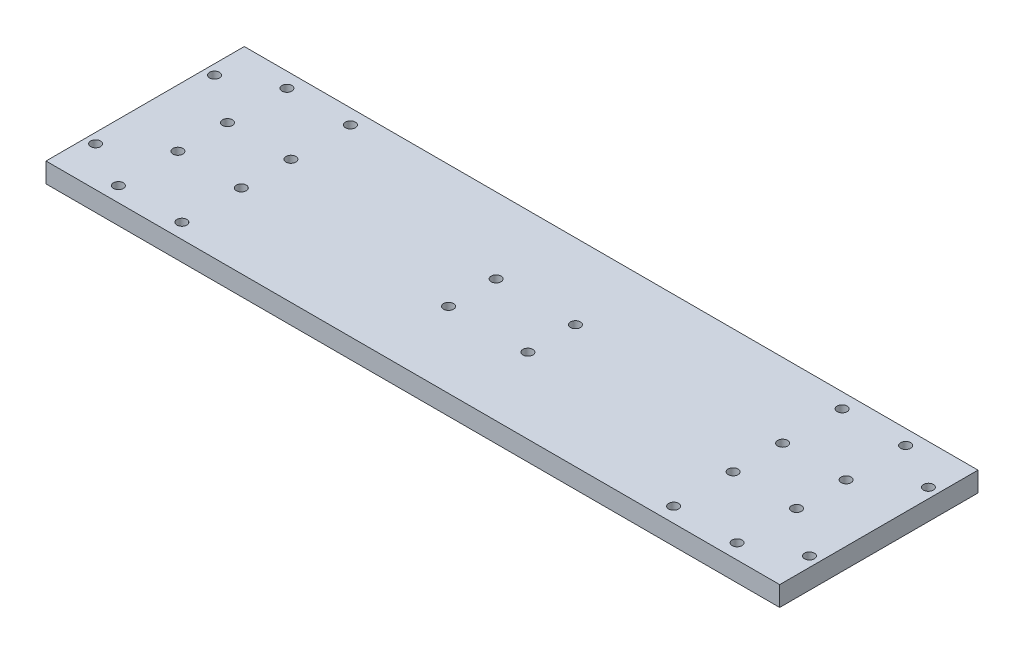
SolidWorks part; units mm, degrees
ref_plane "Front Plane" through (0, 0, 0) normal (0, 0, 1) x (1, 0, 0)
ref_plane "Top Plane" through (0, 0, 0) normal (0, 1, 0) x (1, 0, 0)
ref_plane "Right Plane" through (0, 0, 0) normal (1, 0, 0) x (0, 0, -1)
sketch "Sketch1" plane through (0, 0, 0) normal (0, 1, 0) x (1, 0, 0)
  line L1 (185, -50) -> (-185, -50)
  line L2 (185, -50) -> (185, 50)
  line L3 (185, 50) -> (-185, 50)
  line L4 (-185, -50) -> (-185, 50)
  line L5 (185, -50) -> (-185, 50) construction
  line L6 (185, 50) -> (-185, -50) construction
  point P0 (0, 0)
  dimension "D1" = 100
  dimension "D2" = 370
extrude "Boss-Extrude1" add sketch "Sketch1" along normal blind 10
sketch "Sketch3" plane through (0, 0, 0) normal (0, -1, 0) x (1, 0, 0)
  line L1 (-180, -30) -> (180, -30) construction
  line L2 (-156, 42.5) -> (-156, 50) construction
  line L3 (20, -12) -> (-20, -12) construction
  line L4 (20, -12) -> (20, 12) construction
  line L5 (20, 12) -> (-20, 12) construction
  line L6 (-20, -12) -> (-20, 12) construction
  line L7 (20, -12) -> (-20, 12) construction
  line L8 (20, 12) -> (-20, -12) construction
  line L9 (-185, 50) -> (185, 50) construction
  line L10 (-156, -42.5) -> (-156, -50) construction
  line L11 (185, -50) -> (-185, -50) construction
  line L12 (-156, 42.5) -> (-185, 42.5) construction
  line L13 (-185, -50) -> (-185, 50) construction
  line L14 (156, 42.5) -> (185, 42.5) construction
  line L15 (185, 50) -> (185, -50) construction
  line L16 (-180, -30) -> (-180, 30) construction
  line L17 (-180, 30) -> (180, 30) construction
  line L18 (180, -30) -> (180, 30) construction
  line L19 (-180, -30) -> (180, 30) construction
  line L20 (-180, 30) -> (180, -30) construction
  circle A0 centre (-156, 42.5) radius 2.5
  circle A1 centre (-124, 42.5) radius 2.5
  circle A2 centre (124, 42.5) radius 2.5
  circle A3 centre (156, 42.5) radius 2.5
  circle A4 centre (-156, 12.5) radius 2.5
  circle A5 centre (-124, 12.5) radius 2.5
  circle A6 centre (124, 12.5) radius 2.5
  circle A7 centre (156, 12.5) radius 2.5
  circle A8 centre (-156, -12.5) radius 2.5
  circle A9 centre (-124, -12.5) radius 2.5
  circle A10 centre (124, -12.5) radius 2.5
  circle A11 centre (156, -12.5) radius 2.5
  circle A12 centre (-156, -42.5) radius 2.5
  circle A13 centre (-124, -42.5) radius 2.5
  circle A14 centre (124, -42.5) radius 2.5
  circle A15 centre (156, -42.5) radius 2.5
  circle A16 centre (-20, 12) radius 2.5
  circle A17 centre (20, 12) radius 2.5
  circle A18 centre (20, -12) radius 2.5
  circle A19 centre (-20, -12) radius 2.5
  circle A20 centre (-180, 30) radius 2.5
  circle A21 centre (-180, -30) radius 2.5
  circle A22 centre (180, -30) radius 2.5
  circle A23 centre (180, 30) radius 2.5
  point P2 (0, 0)
  point P30 (0, 0)
  dimension "D4" = 5
  dimension "D9" = 5
  dimension "D1" = 2
  dimension "D5" = 32
  dimension "D6" = 32
  dimension "D7" = 24
  dimension "D8" = 40
  dimension "D10" = 360
  dimension "D11" = 60
  dimension "D2" = 2
  dimension "D3" = 2
extrude "Cut-Extrude1" cut sketch "Sketch3" against normal through all
